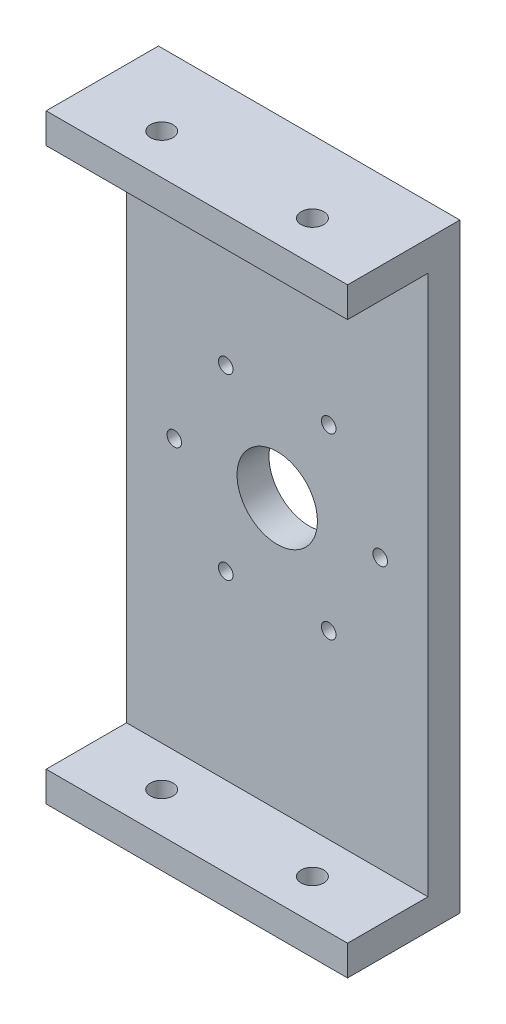
SolidWorks part; units mm, degrees
material "Aleación 6061"
ref_plane "Alzado" through (0, 0, 0) normal (0, 0, 1) x (1, 0, 0)
ref_plane "Planta" through (0, 0, 0) normal (0, 1, 0) x (1, 0, 0)
ref_plane "Vista lateral" through (0, 0, 0) normal (1, 0, 0) x (0, 0, -1)
sketch "Sk_Repisa" plane through (0, 0, 0) normal (0, 0, 1) x (1, 0, 0)
  line L1 (-30, -59.75) -> (30, -59.75)
  line L2 (-30, -59.75) -> (-30, 59.75)
  line L3 (-30, 59.75) -> (30, 59.75)
  line L4 (30, -59.75) -> (30, 59.75)
  line L5 (-30, -59.75) -> (30, 59.75) construction
  line L6 (-30, 59.75) -> (30, -59.75) construction
  point P0 (0, 0)
  dimension "D1" = 60
  dimension "D2" = 119.5
extrude "Repisa" add sketch "Sk_Repisa" along normal blind 6.35 from offset 372.65
sketch "Sk_Centro_motor" plane through (0, 0, 0) normal (0, 0, 1) x (1, 0, 0)
  circle A0 centre (0, 0) radius 8
  dimension "D1" = 16
extrude "Centro_motor" cut sketch "Sk_Centro_motor" along normal blind 6.35 from offset 372.65
sketch "Sk_Pasantes_M2-5_estator_J4" plane through (0, 0, 0) normal (0, 0, 1) x (1, 0, 0)
  circle A0 centre (20.5, 0) radius 1.45
  circle A1 centre (10.25, 17.7535) radius 1.45
  circle A2 centre (-10.25, 17.7535) radius 1.45
  circle A3 centre (-20.5, 0) radius 1.45
  circle A4 centre (-10.25, -17.7535) radius 1.45
  circle A5 centre (10.25, -17.7535) radius 1.45
  dimension "D1" = 2.9
  dimension "D3" = 2.9
  dimension "D6" = 2.9
  dimension "D9" = 2.9
  dimension "D11" = 2.9
  dimension "D14" = 2.9
  dimension "D2" = 20.5
  dimension "D4" = 10.25
  dimension "D5" = 17.7535
  dimension "D7" = 10.25
  dimension "D8" = 17.7535
  dimension "D10" = 20.5
  dimension "D12" = 10.25
  dimension "D13" = 17.7535
  dimension "D15" = 10.25
  dimension "D16" = 17.7535
extrude "Pasantes_M2-5_estator_J4" cut sketch "Sk_Pasantes_M2-5_estator_J4" along normal blind 6.35 from offset 372.65
sketch "Sk_Pestanas" plane through (0, 0, 0) normal (0, 0, 1) x (1, 0, 0)
  line L1 (-30, 53.75) -> (30, 53.75)
  line L2 (-30, 53.75) -> (-30, 59.75)
  line L3 (-30, 59.75) -> (30, 59.75)
  line L4 (30, 53.75) -> (30, 59.75)
  line L5 (-30, 53.75) -> (30, 59.75) construction
  line L6 (-30, 59.75) -> (30, 53.75) construction
  line L7 (-30, -59.75) -> (30, -59.75)
  line L8 (-30, -59.75) -> (-30, -53.75)
  line L9 (-30, -53.75) -> (30, -53.75)
  line L10 (30, -59.75) -> (30, -53.75)
  line L11 (-30, -59.75) -> (30, -53.75) construction
  line L12 (-30, -53.75) -> (30, -59.75) construction
  point P0 (0, 56.75)
  point P6 (0, -56.75)
  dimension "D1" = 60
  dimension "D2" = 6
  dimension "D3" = 56.75
  dimension "D4" = 60
  dimension "D5" = 6
  dimension "D6" = 56.75
extrude "Pestanas" add sketch "Sk_Pestanas" along normal blind 16 from offset 379
sketch "Sk_Pasantes_M4_pestanas" plane through (0, 0, 0) normal (0, 1, 0) x (1, 0, 0)
  circle A0 centre (-15, -387) radius 2.25
  circle A1 centre (15, -387) radius 2.25
  dimension "D1" = 4.5
  dimension "D4" = 4.5
  dimension "D2" = 15
  dimension "D3" = 387
  dimension "D5" = 15
  dimension "D6" = 387
extrude "Pasantes_M4_pestanas" cut sketch "Sk_Pasantes_M4_pestanas" along normal blind 119.5 from offset 59.75
